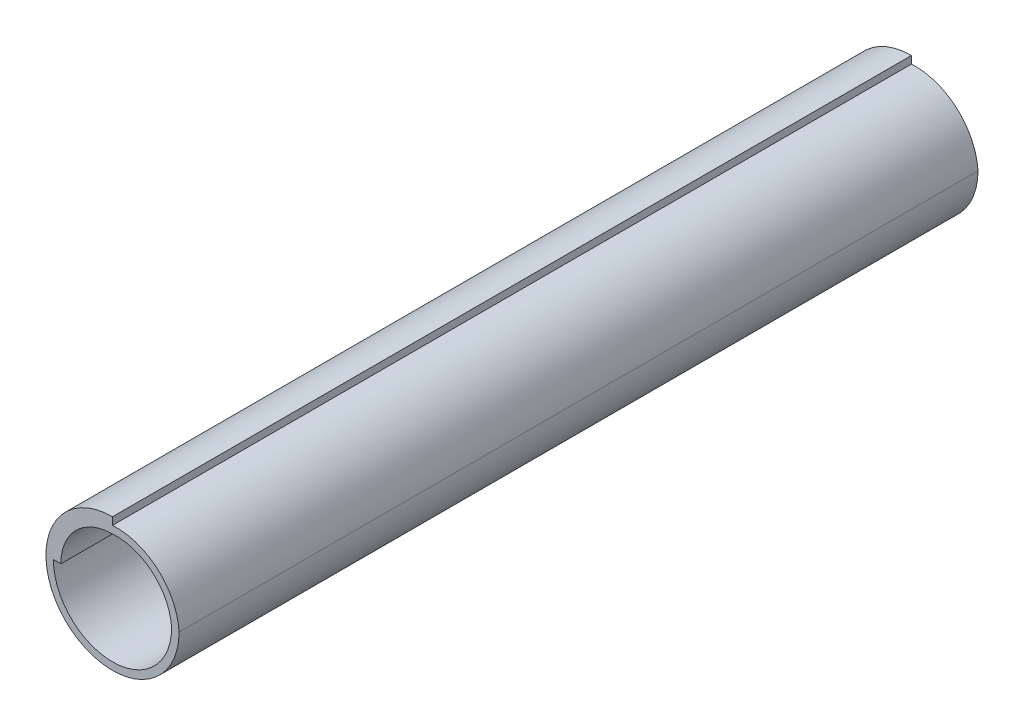
SolidWorks part; units mm, degrees
ref_plane "Plane1" through (0, 0, 0) normal (0, 0, 1) x (1, 0, 0)
ref_plane "Plane2" through (0, 0, 0) normal (0, 1, 0) x (1, 0, 0)
ref_plane "Plane3" through (0, 0, 0) normal (1, 0, 0) x (0, 0, -1)
sketch "Sketch1" plane through (0, 0, 0) normal (0, 0, 1) x (1, 0, 0)
  line L0 (0, 2.22) -> (0, 2.5)
  line L1 (-2.22, 0) -> (-1.94, 0)
  line L2 (0, 1.94) -> (2.22, 0) construction
  line L3 (0.14, -0.14) -> (1.11, 0.97) construction
  line L4 (0, 2.22) -> (2.5, 0) construction
  line L5 (0.14, -0.14) -> (1.25, 1.11) construction
  arc A0 (0, 2.5) -> (2.5, 0) centre (0, 0) ccw
  arc A1 (-2.22, 0) -> (2.22, 0) centre (0, 0) ccw
  arc A2 (0, 1.94) -> (-1.94, 0) centre (0, 0) ccw
  arc A3 (2.22, 0) -> (0, 1.94) centre (0.14, -0.14) ccw
  arc A4 (2.5, 0) -> (0, 2.22) centre (0.14, -0.14) ccw
  dimension "Diameter" = 5
  dimension "D2" = 4.44
  dimension "Thickness" = 0.28
  dimension "D1" = 0.28
extrude "Base-Extrude" add sketch "Sketch1" along normal mid plane 30
equation "\"D1@Sketch1\" = \"Thickness@Sketch1\""
equation "\"D2@Sketch1\" = \"Diameter@Sketch1\" - \"Thickness@Sketch1\" * 2"
